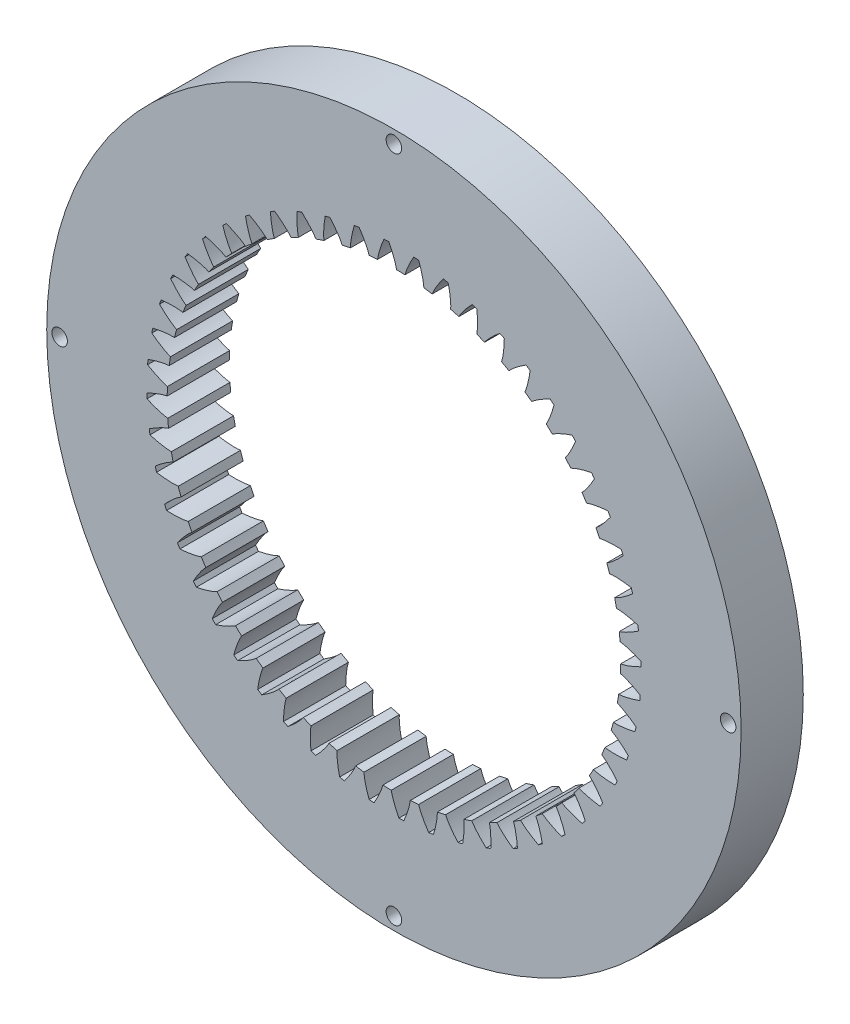
SolidWorks part; units mm, degrees
ref_plane "Front Plane" through (0, 0, 0) normal (0, 0, 1) x (1, 0, 0)
ref_plane "Top Plane" through (0, 0, 0) normal (0, 1, 0) x (1, 0, 0)
ref_plane "Right Plane" through (0, 0, 0) normal (1, 0, 0) x (0, 0, -1)
sketch "Sketch1" plane through (0, 0, 0) normal (1, 0, 0) x (0, 0, -1)
  line L0 (0, 0) -> (-86.9368, 0) construction
  line L1 (-6, 0) -> (-6, 67)
  line L5 (6, 67) -> (-6, 67)
  line L7 (-6, 0) -> (6, 0)
  line L9 (6, 67) -> (6, 0)
  line L11 (23.375, 67) -> (6, 67) construction
  line L12 (23.375, 67) -> (6, 67) construction
  point P6 (0, 0)
  dimension "D2" = 12
revolve "Revolve1" add sketch "Sketch1" angle 360 about L0
sketch "Sketch2" plane through (0, 0, 6) normal (0, 0, 1) x (1, 0, 0)
  line L0 (0, 0) -> (0, 45.5) construction
  line L1 (0, 45.5) -> (-14.6234, 40.1775)
  line L2 (-14.6234, 40.1775) -> (0, 0) construction
  circle A0 centre (0, 0) radius 43.75 construction
  circle A1 centre (0, 0) radius 45.5 construction
  circle A2 centre (0, 0) radius 47.6875 construction
  circle A3 centre (0, 0) radius 42.756 construction
  arc A4 (0.6372, 42.7513) -> (-14.6234, 40.1775) centre (0, 0) ccw
  dimension "D1" = 91
  dimension "D2" = 95.375
  dimension "D3" = 87.5
  dimension "D4" = 20
sketch "Sketch3" plane through (0, 0, 6) normal (0, 0, 1) x (1, 0, 0)
  line L0 (0, 45.5) -> (-14.6234, 40.1775) construction
  line L1 (0, 45.5) -> (-14.6234, 40.1775)
  line L2 (-7.1105, 42.1606) -> (0.5621, 43.4546) construction
  line L3 (-21.6533, 36.8675) -> (-1.5254, 48.6892) construction
  line L4 (-27.9681, 32.3398) -> (-4.4267, 52.6989) construction
  line L5 (-33.3592, 26.744) -> (-9.0242, 57.0984) construction
  arc A0 (-14.6234, 40.1775) -> (-21.6533, 36.8675) centre (0, 0) ccw
  arc A1 (0.6372, 42.7513) -> (-7.1105, 42.1606) centre (0, 0) ccw
  arc A2 (-7.1105, 42.1606) -> (-14.6234, 40.1775) centre (0, 0) ccw
  arc A3 (-21.6533, 36.8675) -> (-27.9681, 32.3398) centre (0, 0) ccw
  arc A4 (-27.9681, 32.3398) -> (-33.3592, 26.744) centre (0, 0) ccw
  circle A5 centre (0, 0) radius 42.756 construction
  dimension "D2" = 7.781
  dimension "D3" = 15.5619
  dimension "D4" = 23.3429
  dimension "D5" = 31.1238
  dimension "D6" = 38.9048
  dimension "D1" = 7.781
sketch "Sketch4" plane through (0, 0, 6) normal (0, 0, 1) x (1, 0, 0)
  line L0 (0, 0) -> (-1.1193, 37.042) construction
  line L1 (0, 0) -> (0, 45.5) construction
  arc A0 (-3.1509, 43.6364) -> (0.5105, 43.747) centre (0, 0) cw
  circle A1 centre (0, 0) radius 43.75 construction
  arc A2 (-1.9133, 47.6491) -> (-0.9672, 47.6777) centre (0, 0) cw
  circle A4 centre (0, 0) radius 47.6875 construction
  spline S0 degree 3 poles (-9.0242, 57.0984) (-6.1134, 54.737) (-2.593, 51.0725) (0.0059, 45.7587) (0.5859, 43.6957) (0.6372, 42.7513) knots 0 0 0 0 0.639984 0.839981 1 1 1 1
  spline S1 degree 3 poles (5.5602, 57.5391) (2.7973, 55.0062) (-0.4954, 51.1359) (-2.7687, 45.6749) (-3.2231, 43.5806) (-3.2173, 42.6348) knots 0 0 0 0 0.639984 0.839981 1 1 1 1
  dimension "D1" = 1.731
extrude "Cut-Extrude1" cut sketch "Sketch4" against normal through all
pattern_circular "CirPattern1" count 52 over 360 about axis through (0, 0, -6) along (0, 0, 1) of "Cut-Extrude1"
sketch "Sketch5" plane through (0, 0, 6) normal (0, 0, 1) x (1, 0, 0)
  circle A0 centre (0, 0) radius 43.75 construction
  circle A1 centre (0, 0) radius 43.75
extrude "Cut-Extrude2" cut sketch "Sketch5" against normal through all
sketch "Sketch6" plane through (0, 0, 6) normal (0, 0, 1) x (1, 0, 0)
  circle A0 centre (64.5, 0) radius 1.5 construction
  circle A1 centre (0, 64.5) radius 1.5 construction
  circle A2 centre (-64.5, 0) radius 1.5 construction
  circle A3 centre (0, -64.5) radius 1.5 construction
  circle A4 centre (64.5, 0) radius 1.5
  circle A5 centre (0, 64.5) radius 1.5
  circle A6 centre (-64.5, 0) radius 1.5
  circle A7 centre (0, -64.5) radius 1.5
extrude "Cut-Extrude3" cut sketch "Sketch6" against normal through all
equation "\"D1@Sketch2\"=\"Ring Teeth@Wheel Assembly.Assembly\"*\"Module@Wheel Assembly.Assembly\""
equation "\"D2@Sketch2\" = \"D1@Sketch2\" + 2 * \"Dedendum@Wheel Assembly.Assembly\""
equation "\"D3@Sketch2\"=\"D1@Sketch2\"-2*\"Addendum@Wheel Assembly.Assembly\""
equation "\"D2@Sketch3\"=\"D3@Sketch3\"-\"D1@Sketch3\""
equation "\"D4@Sketch3\"=\"D3@Sketch3\"+\"D1@Sketch3\""
equation "\"D5@Sketch3\"=\"D4@Sketch3\"+\"D1@Sketch3\""
equation "\"D6@Sketch3\"=\"D5@Sketch3\"+\"D1@Sketch3\""
equation "\"D1@Sketch4\"=90/\"Ring Teeth@Wheel Assembly.Assembly\""
equation "\"D1@CirPattern1\"=\"Ring Teeth@Wheel Assembly.Assembly\""
